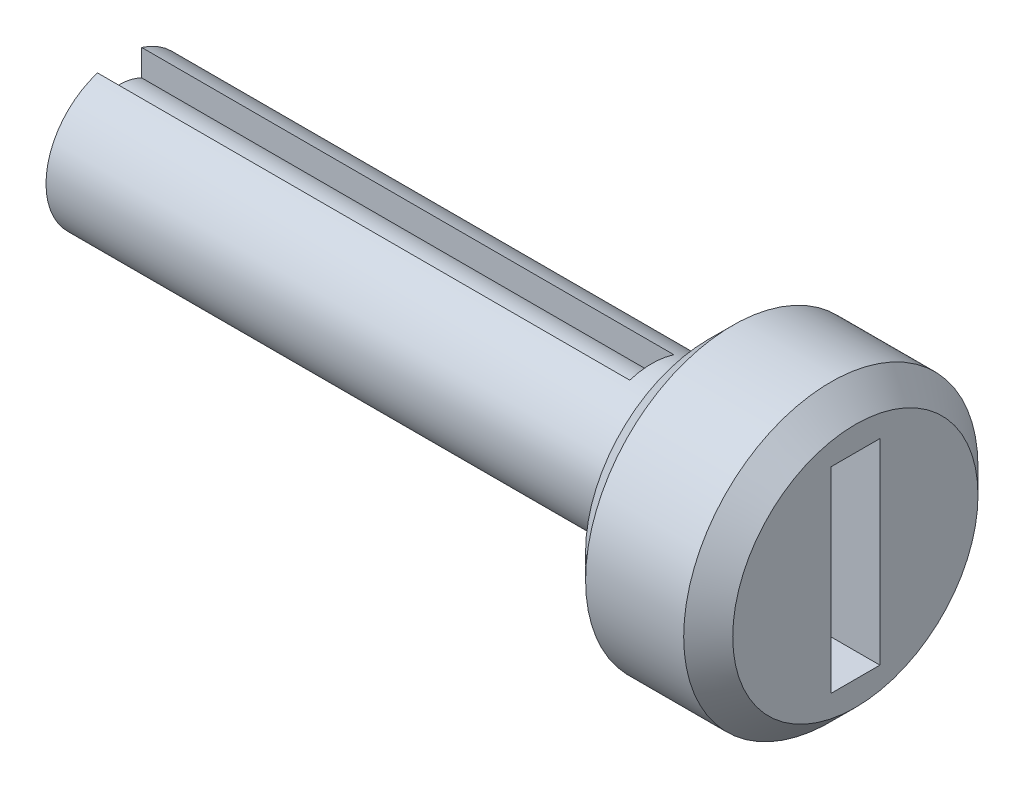
SolidWorks part; units mm, degrees
ref_plane "Front Plane" through (0, 0, 0) normal (0, 0, 1) x (1, 0, 0)
ref_plane "Top Plane" through (0, 0, 0) normal (0, 1, 0) x (1, 0, 0)
ref_plane "Right Plane" through (0, 0, 0) normal (1, 0, 0) x (0, 0, -1)
sketch "Sketch2" plane through (0, 0, 0) normal (0, 1, 0) x (1, 0, 0)
  line L0 (0, 0) -> (0, 3)
  line L1 (0, 3) -> (24, 3)
  line L2 (24, 3) -> (24, 6)
  line L3 (24, 6) -> (30, 6)
  line L4 (30, 6) -> (30, 0)
  line L5 (30, 0) -> (0, 0)
  line L6 (0, 0) -> (33.3109, 0) construction
  dimension "D1" = 30
  dimension "D2" = 6
  dimension "D3" = 6
  dimension "D4" = 12
revolve "Revolve1" add sketch "Sketch2" angle 360 about L6
sketch "Sketch3" plane through (0, 0, 0) normal (-1, 0, 0) x (0, 0, 1)
  circle A0 centre (0, 0) radius 1.2
  dimension "D1" = 2.4
extrude "Cut-Extrude1" cut sketch "Sketch3" against normal up to surface (24 mm away) up to face at (24, 0, 3)
cosmetic thread "Cosmetic Thread1" parameters "D2"=3
sketch "Sketch4" plane through (30, 0, 0) normal (1, 0, 0) x (0, 0, -1)
  line L1 (-1, -4) -> (1, -4)
  line L2 (-1, -4) -> (-1, 4)
  line L3 (-1, 4) -> (1, 4)
  line L4 (1, -4) -> (1, 4)
  line L5 (-1, -4) -> (1, 4) construction
  line L6 (-1, 4) -> (1, -4) construction
  point P0 (0, 0)
  dimension "D1" = 2
  dimension "D2" = 8
extrude "Cut-Extrude2" cut sketch "Sketch4" against normal blind 4
chamfer "Chamfer1" distance 1 angle 45 2 edges at (30, 0, 6) (24, 0, 6)
sketch "Sketch5" plane through (0, 0, 0) normal (-1, 0, 0) x (0, 0, 1)
  line L0 (-0.9, 2.3239) -> (0.9, 2.3239) construction
  line L1 (0, 2.3239) -> (0, 0) construction
  line L2 (-0.9, 2.8618) -> (-0.9, 1.7861)
  line L3 (0, 0) -> (0, -2.3239) construction
  line L4 (0.9, 2.8618) -> (0.9, 1.7861)
  line L5 (-0.9, -2.3239) -> (0.9, -2.3239) construction
  line L6 (-0.9, -1.7861) -> (-0.9, -2.8618)
  line L8 (0.9, -1.7861) -> (0.9, -2.8618)
  circle A0 centre (0, 0) radius 3 construction
  arc A1 (0.9, 2.8618) -> (-0.9, 2.8618) centre (0, 0) ccw
  arc A4 (-0.9, -2.8618) -> (0.9, -2.8618) centre (0, 0) ccw
  arc A6 (0.9, 1.7861) -> (-0.9, 1.7861) centre (0, 0) ccw
  arc A7 (-0.9, -1.7861) -> (0.9, -1.7861) centre (0, 0) ccw
  point P11 (0, -2.3239)
  dimension "D2" = 4
  dimension "D1" = 1.8
extrude "Cut-Extrude3" cut sketch "Sketch5" against normal offset from surface (21.7 mm away) 2.3 up to face at (24, 0, -5)
